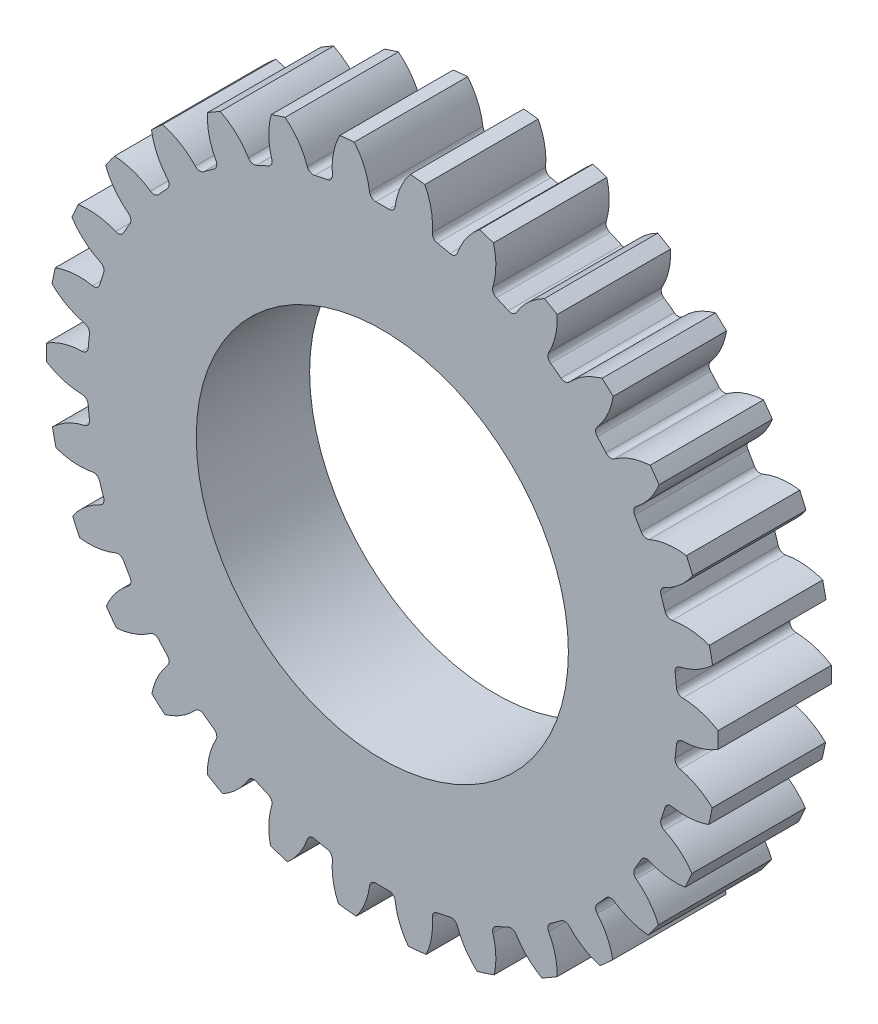
SolidWorks part; units mm, degrees
ref_plane "Front Plane" through (0, 0, 0) normal (0, 0, 1) x (1, 0, 0)
ref_plane "Top Plane" through (0, 0, 0) normal (0, 1, 0) x (1, 0, 0)
ref_plane "Right Plane" through (0, 0, 0) normal (1, 0, 0) x (0, 0, -1)
sketch "Sketch1" plane through (0, 0, 0) normal (0, 0, 1) x (1, 0, 0)
  circle A0 centre (0, 0) radius 25
  circle A1 centre (0, 0) radius 23.33
  circle A2 centre (0, 0) radius 26.665
  dimension "D1" = 50
  dimension "D2" = 53.33
  dimension "D3" = 46.66
extrude "Boss-Extrude1" add sketch "Sketch1" along normal mid plane 9 contours A2
sketch "Sketch2" plane through (0, 0, 0) normal (0, 0, 1) x (1, 0, 0)
  line L0 (0, 0) -> (0, 26.665) construction
  line L1 (-1.3084, 24.9657) -> (1.3084, 24.9657) construction
  line L2 (0, 21.3709) -> (-2.2573, 27.5728) construction
  line L3 (0, 0) -> (-0.9803, 23.3094) construction
  line L4 (0, 0) -> (2.7873, 26.5189) construction
  line L5 (1.3084, 24.9657) -> (3.9109, 24.6922) construction
  circle A0 centre (0, 0) radius 23.33 construction
  arc A1 (0.9803, 23.3094) -> (-0.9803, 23.3094) centre (0, 0) ccw
  circle A2 centre (0, 0) radius 26.665 construction
  arc A3 (-0.9803, 23.3094) -> (-3.1688, 27.4829) centre (-6.4966, 23.0774) ccw
  arc A4 (0.9803, 23.3094) -> (3.1688, 27.4829) centre (6.4966, 23.0774) cw
  circle A6 centre (0, 0) radius 25 construction
  circle A7 centre (0, 0) radius 27.665
  arc A8 (3.1688, 27.4829) -> (-3.1688, 27.4829) centre (0, 0) ccw
  dimension "D2" = 20
  dimension "D3" = 6
  dimension "D1" = 1
extrude "Cut-Extrude1" cut sketch "Sketch2" against normal mid plane 16.67
fillet "Fillet1" radius 0.5 2 edges at (0.9803, 23.3094, 0) (-0.9803, 23.3094, 0)
pattern_circular "CirPattern1" count 30 over 360 about axis through (0, -0.1053, 0) along (0, 0, 1) of "Cut-Extrude1", "Fillet1"
sketch "Sketch3" plane through (0, 0, 4.5) normal (0, 0, 1) x (1, 0, 0)
  circle A0 centre (0, 0) radius 13
  dimension "D1" = 26
extrude "Cut-Extrude2" cut sketch "Sketch3" against normal through all
scale "Scale1" bodies to scale 104 scale about centroid uniform scaling yes scale factor 0.88
sketch "Sketch4" plane through (0, 0, 3.96) normal (0, 0, 1) x (1, 0, 0)
  circle A0 centre (0, -0.0128) radius 13
  dimension "D1" = 26
extrude "Cut-Extrude3" cut sketch "Sketch4" against normal blind 10
equation "\"M\"= 1.6666'modül"
equation "\"z\"= 30'dişli sayısı"
equation "\"b\"= \"M\" * 10'dlşli genişliği"
equation "\"d0\"= \"M\" * \"z\"'bölüm daire çapı"
equation "\"da\"= \"M\" * ( \"z\" + 2 )'DİŞ ÜST ÇAPI"
equation "\"df\"= \"M\" * ( \"z\" - 2 )'diş dipi çapı"
equation "\"r\"= \"M\" * 0.3'neyse"
equation "\"q\"= 20deg'kuvvet açısı"
equation "\"y\"= 180 / 30'tasarım açısı"
